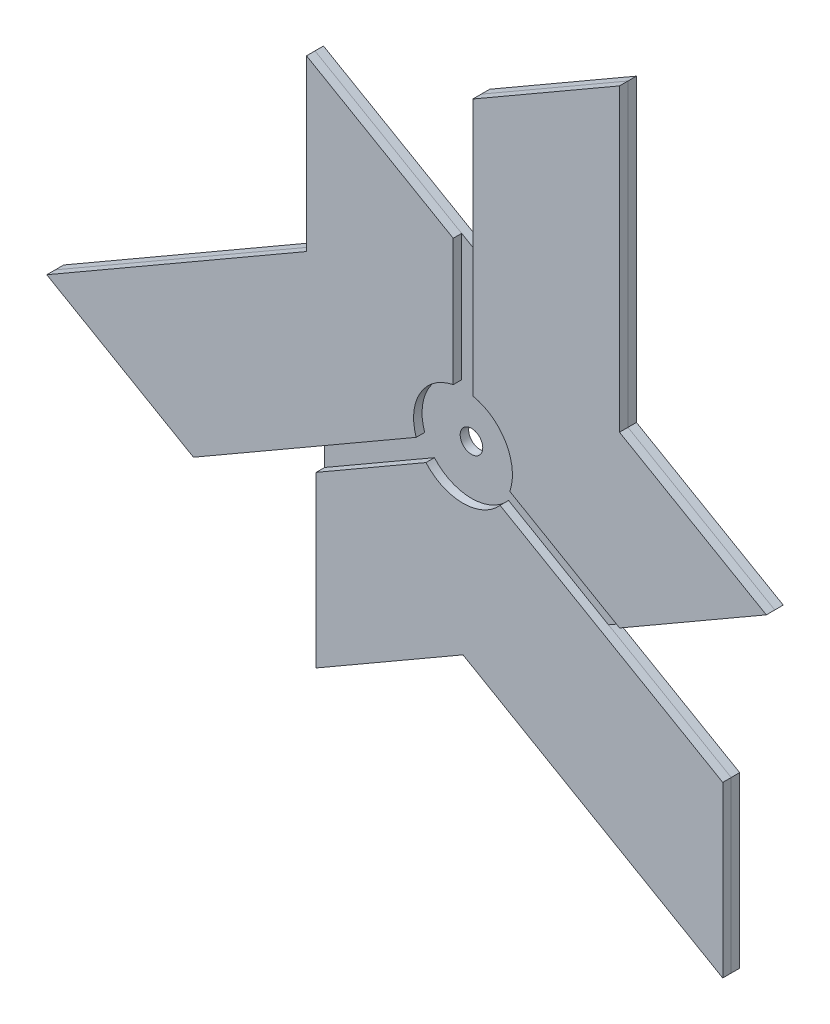
SolidWorks part; units mm, degrees
ref_plane "Front Plane" through (0, 0, 0) normal (0, 0, 1) x (1, 0, 0)
ref_plane "Top Plane" through (0, 0, 0) normal (0, 1, 0) x (1, 0, 0)
ref_plane "Right Plane" through (0, 0, 0) normal (1, 0, 0) x (0, 0, -1)
sketch "Sketch1" plane through (0, 0, 0) normal (0, 0, 1) x (1, 0, 0)
  line L0 (0, 0) -> (0, 166.3044) construction
  line L1 (-28, -28) -> (28, -28) construction
  line L2 (-28, -28) -> (-28, 28) construction
  line L3 (-28, 28) -> (28, 28) construction
  line L4 (28, -28) -> (28, 28) construction
  line L5 (-28, -28) -> (28, 28) construction
  line L6 (-28, 28) -> (28, -28) construction
  line L7 (0, 0) -> (-99.4913, -57.4413) construction
  line L8 (0, 0) -> (107.254, -61.9231) construction
  line L9 (-52, -34.0222) -> (-13.1235, -11.5769)
  line L10 (-16.6356, -5.432) -> (-95.9418, -51.2195)
  line L11 (0, 0) -> (0, -84.3214) construction
  line L12 (0, 0) -> (92.3752, 53.3328) construction
  line L13 (0, 0) -> (-117.8209, 68.0239) construction
  line L14 (-52, -34.0222) -> (-52, -94.0222)
  line L15 (-52, -94.0222) -> (0, -64)
  line L16 (0, -64) -> (92, -117.1162)
  line L17 (92, -117.1162) -> (92, -57.1162)
  line L18 (92, -57.1162) -> (13.1235, -11.5769)
  circle A0 centre (0, 0) radius 150 construction
  circle A1 centre (0, 0) radius 17.5
  dimension "D1" = 300
  dimension "D6" = 35
  dimension "D2" = 56
  dimension "D3" = 56
  dimension "D4" = 120
  dimension "D5" = 120
  dimension "D7" = 60
  dimension "D8" = 60
  dimension "D9" = 52
  dimension "D10" = 60
  dimension "D11" = 60
  dimension "D12" = 64
  dimension "D13" = 92
extrude "Boss-Extrude1" add sketch "Sketch1" along normal blind 3 contours A1 L9 L14 L15 L16 L17 L18
pattern_circular "CirPattern2" count 3 over 360 about axis through (0, 0, 0) along (0, 0, 1) of bodies 101
sketch "Sketch6" plane through (0, 0, 3) normal (0, 0, 1) x (1, 0, 0)
  line L0 (-55.4256, 92.0444) -> (-55.4256, 32)
  line L1 (-55.4256, 32) -> (-147.4256, -21.1162)
  line L2 (-147.4256, -21.1162) -> (-95.4641, -51.1162)
  line L3 (-95.4641, -51.1162) -> (-52, -26.0222)
  line L4 (-95.4641, -51.1162) -> (-16.5876, -5.5769) construction
  line L5 (-52, -26.0222) -> (-52, -94.0222)
  line L6 (-52, -94.0222) -> (0, -64)
  line L7 (0, -64) -> (92, -117.1162)
  line L8 (92, -117.1162) -> (92, -57.1162)
  line L9 (92, -57.1162) -> (48.5359, -32.0222)
  line L10 (92, -57.1162) -> (13.1235, -11.5769) construction
  line L11 (48.5359, -32.0222) -> (107.4256, 1.9778)
  line L12 (107.4256, 1.9778) -> (55.4256, 32)
  line L13 (55.4256, 32) -> (55.4256, 138.2324)
  line L14 (55.4256, 138.2324) -> (3.4641, 108.2324)
  line L15 (3.4641, 108.2324) -> (3.4641, 58.0444)
  line L16 (3.4641, 108.2324) -> (3.4641, 17.1537) construction
  line L17 (3.4641, 58.0444) -> (-55.4256, 92.0444)
  line L18 (-3.4641, 62.0444) -> (-55.4256, 92.0444) construction
  line L19 (55.4641, -28.0222) -> (107.4256, 1.9778) construction
  line L20 (-52, -34.0222) -> (-52, -94.0222) construction
  circle A0 centre (0, 0) radius 4
  dimension "D1" = 8
extrude "Boss-Extrude2" add sketch "Sketch6" along normal blind 3 from offset 6 separate body
